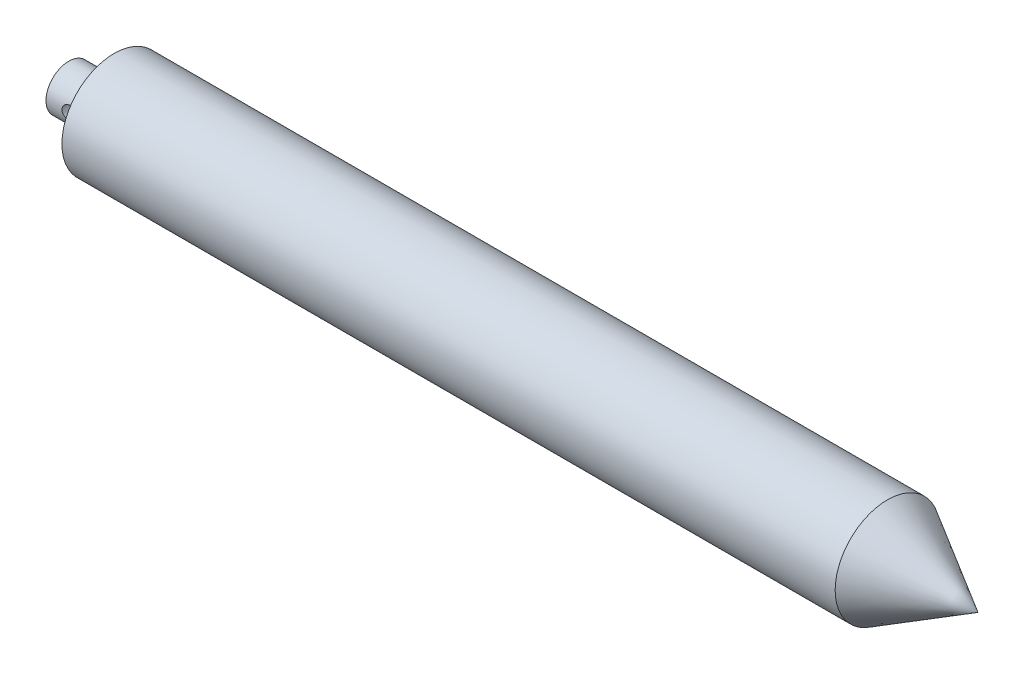
SolidWorks part; units mm, degrees
ref_plane "Front Plane" through (0, 0, 0) normal (0, 0, 1) x (1, 0, 0)
ref_plane "Top Plane" through (0, 0, 0) normal (0, 1, 0) x (1, 0, 0)
ref_plane "Right Plane" through (0, 0, 0) normal (1, 0, 0) x (0, 0, -1)
sketch "Sketch1" plane through (0, 0, 0) normal (0, 0, 1) x (1, 0, 0)
  line L0 (0, 0) -> (200, 0) construction
  line L1 (0, 0) -> (0, 5)
  line L2 (0, 5) -> (10, 5)
  line L3 (180.0814, 11.5) -> (200, 0)
  line L4 (0, 0) -> (200, 0)
  line L5 (10, 5) -> (10, 11.5)
  line L6 (10, 11.5) -> (180.0814, 11.5)
  dimension "D1" = 30
  dimension "D2" = 11.5
  dimension "D3" = 5
  dimension "D4" = 10
  dimension "D5" = 200
revolve "Corpo" add sketch "Sketch1" angle 360 about L0
ref_plane "Plano de Referência" through (0, 0, 5) normal (0, 0, 1) x (1, 0, 0)
sketch "Posição do Furo" plane through (0, 0, 5) normal (0, 0, 1) x (1, 0, 0)
  line L0 (0, 0) -> (10, 0) construction
  line L1 (10, 5) -> (10, -5) construction
  circle A0 centre (5, 0) radius 1.5
  dimension "D1" = 3
extrude "Furo Ø3 Passante" cut sketch "Posição do Furo" against normal through all
